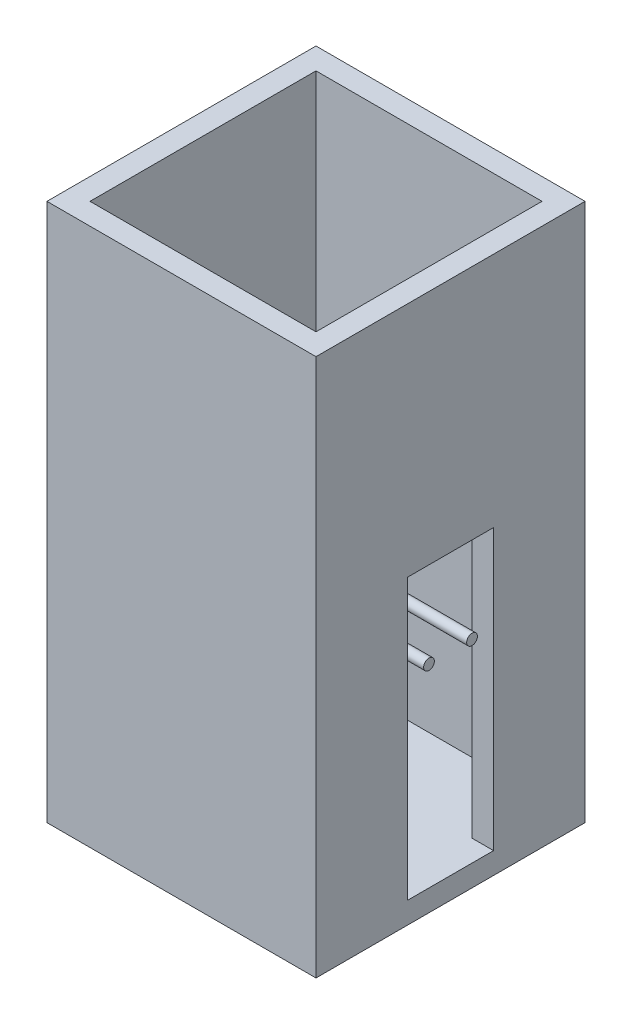
SolidWorks part; units mm, degrees
ref_plane "Front Plane" through (0, 0, 0) normal (0, 0, 1) x (1, 0, 0)
ref_plane "Top Plane" through (0, 0, 0) normal (0, 1, 0) x (1, 0, 0)
ref_plane "Right Plane" through (0, 0, 0) normal (1, 0, 0) x (0, 0, -1)
sketch "Sketch4" plane through (0, 0, 0) normal (0, 1, 0) x (1, 0, 0)
  line L1 (-39.6875, -39.6875) -> (39.6875, -39.6875)
  line L2 (-39.6875, -39.6875) -> (-39.6875, 39.6875)
  line L3 (-39.6875, 39.6875) -> (39.6875, 39.6875)
  line L4 (39.6875, -39.6875) -> (39.6875, 39.6875)
  line L5 (-39.6875, -39.6875) -> (39.6875, 39.6875) construction
  line L6 (-39.6875, 39.6875) -> (39.6875, -39.6875) construction
  point P0 (0, 0)
  dimension "D1" = 79.375
  dimension "D2" = 79.375
extrude "Boss-Extrude3" add sketch "Sketch4" along normal blind 6.35
sketch "Sketch5" plane through (0, 6.35, 0) normal (0, 1, 0) x (1, 0, 0)
  line L0 (-33.3375, -33.3375) -> (-33.3375, 33.3375)
  line L1 (-39.6875, -39.6875) -> (39.6875, -39.6875)
  line L2 (-39.6875, -39.6875) -> (-39.6875, 39.6875)
  line L3 (-39.6875, 39.6875) -> (39.6875, 39.6875)
  line L4 (39.6875, -39.6875) -> (39.6875, 39.6875)
  line L5 (-39.6875, -39.6875) -> (39.6875, 39.6875) construction
  line L6 (-39.6875, 39.6875) -> (39.6875, -39.6875) construction
  line L7 (-33.3375, 33.3375) -> (33.3375, 33.3375)
  line L8 (33.3375, -33.3375) -> (33.3375, 33.3375)
  line L9 (-33.3375, -33.3375) -> (33.3375, -33.3375)
  point P0 (0, 0)
  dimension "D1" = 6.35
extrude "Boss-Extrude4" add sketch "Sketch5" along normal blind 152.4
sketch "Sketch7" plane through (39.6875, 0, 0) normal (1, 0, 0) x (0, 0, -1)
  line L0 (0, 0) -> (0, 90.1262) construction
  line L1 (-39.6875, 0) -> (39.6875, 0) construction
  line L2 (-33.3375, 6.35) -> (33.3375, 6.35) construction
  line L3 (12.7, 6.35) -> (-12.7, 6.35)
  line L4 (12.7, 6.35) -> (12.7, 88.9)
  line L5 (12.7, 88.9) -> (-12.7, 88.9)
  line L6 (-12.7, 6.35) -> (-12.7, 88.9)
  line L7 (12.7, 6.35) -> (-12.7, 88.9) construction
  line L8 (12.7, 88.9) -> (-12.7, 6.35) construction
  point P4 (0, 47.625)
  dimension "D1" = 82.55
  dimension "D2" = 25.4
extrude "Cut-Extrude1" cut sketch "Sketch7" against normal up to surface (6.35 mm away) up to face at (33.3375, 82.55, 0)
sketch "Sketch8" plane through (-33.3375, 0, 0) normal (1, 0, 0) x (0, 0, -1)
  line L0 (0, 0) -> (0, 156.7732) construction
  line L1 (12.7, 88.9) -> (-12.7, 88.9) construction
  line L2 (-4.7625, 63.5) -> (-4.7625, 6.35) construction
  line L3 (4.7625, 63.5) -> (4.7625, 6.35) construction
  line L4 (-12.7, 6.35) -> (12.7, 6.35) construction
  circle A0 centre (-6.35, 63.5) radius 1.5875
  circle A1 centre (6.35, 63.5) radius 1.5875
  point P8 (0, 88.9)
  dimension "D1" = 3.175
  dimension "D3" = 9.525
  dimension "D4" = 57.15
extrude "Boss-Extrude5" add sketch "Sketch8" along normal up to surface (73.025 mm away) up to face at (39.6875, 47.625, 0)
